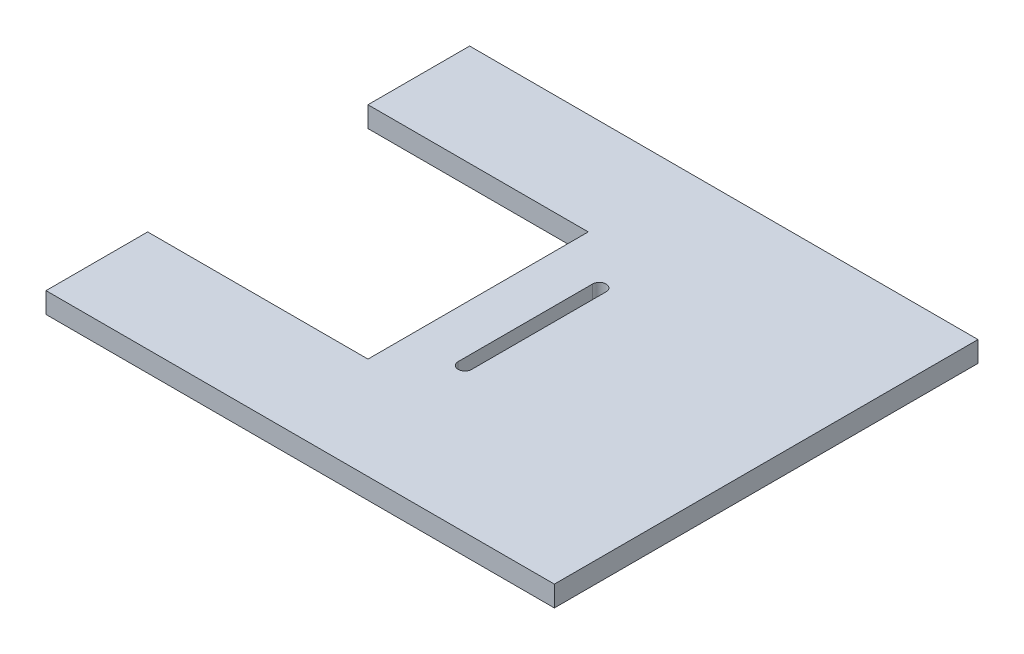
SolidWorks part; units mm, degrees
ref_plane "Front Plane" through (0, 0, 0) normal (0, 0, 1) x (1, 0, 0)
ref_plane "Top Plane" through (0, 0, 0) normal (0, 1, 0) x (1, 0, 0)
ref_plane "Right Plane" through (0, 0, 0) normal (1, 0, 0) x (0, 0, -1)
sketch "Sketch1" plane through (0, 0, 0) normal (0, 1, 0) x (1, 0, 0)
  line L1 (-150, 125) -> (150, 125)
  line L2 (-150, 125) -> (-150, -125)
  line L3 (-150, -125) -> (150, -125)
  line L4 (150, 125) -> (150, -125)
  line L5 (-150, 125) -> (150, -125) construction
  line L6 (-150, -125) -> (150, 125) construction
  line L7 (-150, 65) -> (-20, 65)
  line L8 (-150, 65) -> (-150, -65)
  line L9 (-150, -65) -> (-20, -65)
  line L10 (-20, 65) -> (-20, -65)
  point P0 (0, 0)
  point P10 (-20, 0)
  point P11 (-150, 0)
  dimension "D1" = 250
  dimension "D2" = 300
  dimension "D3" = 130
  dimension "D4" = 130
extrude "Boss-Extrude2" add sketch "Sketch1" along normal blind 12.2 contours L7 L10 L9 L2 L3 L4 L1
sketch "Sketch2" plane through (0, 12.2, 0) normal (0, 1, 0) x (1, 0, 0)
  line L0 (11.8844, 39.6548) -> (11.8844, -39.6548) construction
  line L1 (15.8844, 39.6548) -> (15.8844, -39.6548)
  line L2 (7.8844, 39.6548) -> (7.8844, -39.6548)
  arc A3 (15.8844, 39.6548) -> (7.8844, 39.6548) centre (11.8844, 39.6548) ccw
  arc A4 (7.8844, -39.6548) -> (15.8844, -39.6548) centre (11.8844, -39.6548) ccw
  point P1 (11.8844, 0)
  point P2 (11.8844, 0)
  dimension "D1" = 4
extrude "Cut-Extrude1" cut sketch "Sketch2" against normal blind 30
